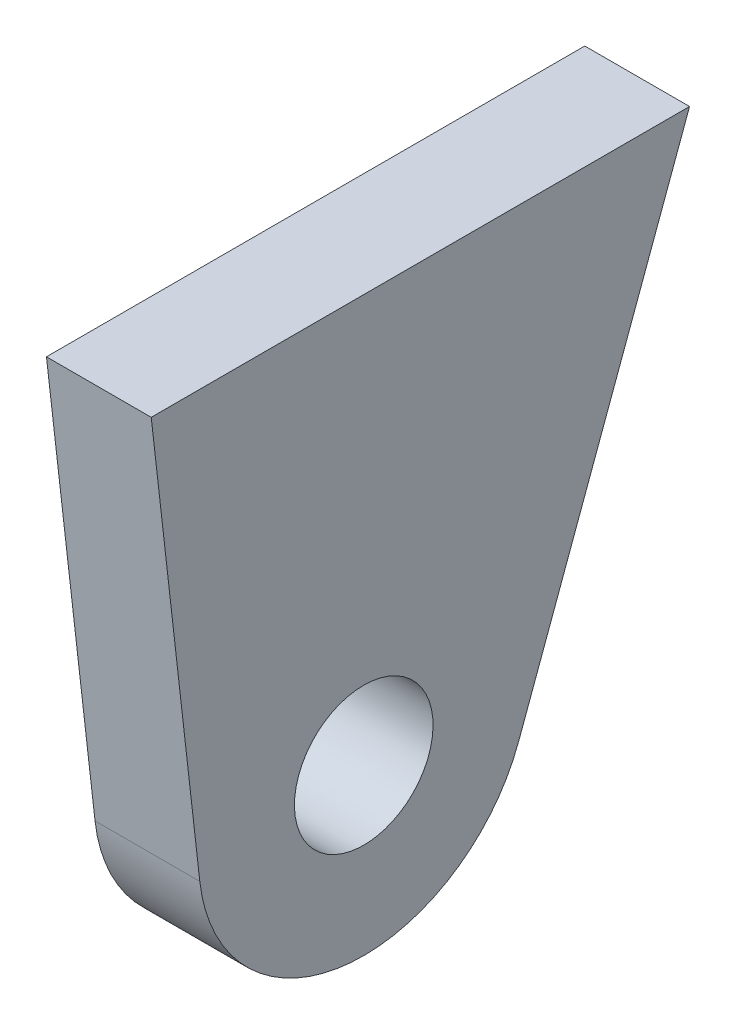
SolidWorks part; units mm, degrees
material "AISI 4130 Steel, normalized at 870C"
ref_plane "Front Plane" through (0, 0, 0) normal (0, 0, 1) x (1, 0, 0)
ref_plane "Top Plane" through (0, 0, 0) normal (0, 1, 0) x (1, 0, 0)
ref_plane "Right Plane" through (0, 0, 0) normal (1, 0, 0) x (0, 0, -1)
sketch "Sketch2" plane through (-106.215, 0, 0) normal (1, 0, 0) x (0, 0, -1)
  line L3 (916.7136, -360.6774) -> (927.0751, -332.5236)
  line L4 (927.0751, -332.5236) -> (894.4484, -332.5236)
  line L5 (894.4484, -332.5236) -> (897.3933, -358.3563)
  circle A0 centre (907.329, -357.2236) radius 4.2
  arc A4 (916.7136, -360.6774) -> (897.3933, -358.3563) centre (907.329, -357.2236) cw
  dimension "D1" = 8.4
  dimension "D5" = 26
  dimension "D3" = 10
  dimension "D4" = 30
  dimension "D2" = 24.7
extrude "Boss-Extrude2" add sketch "Sketch2" along normal blind 6.35
